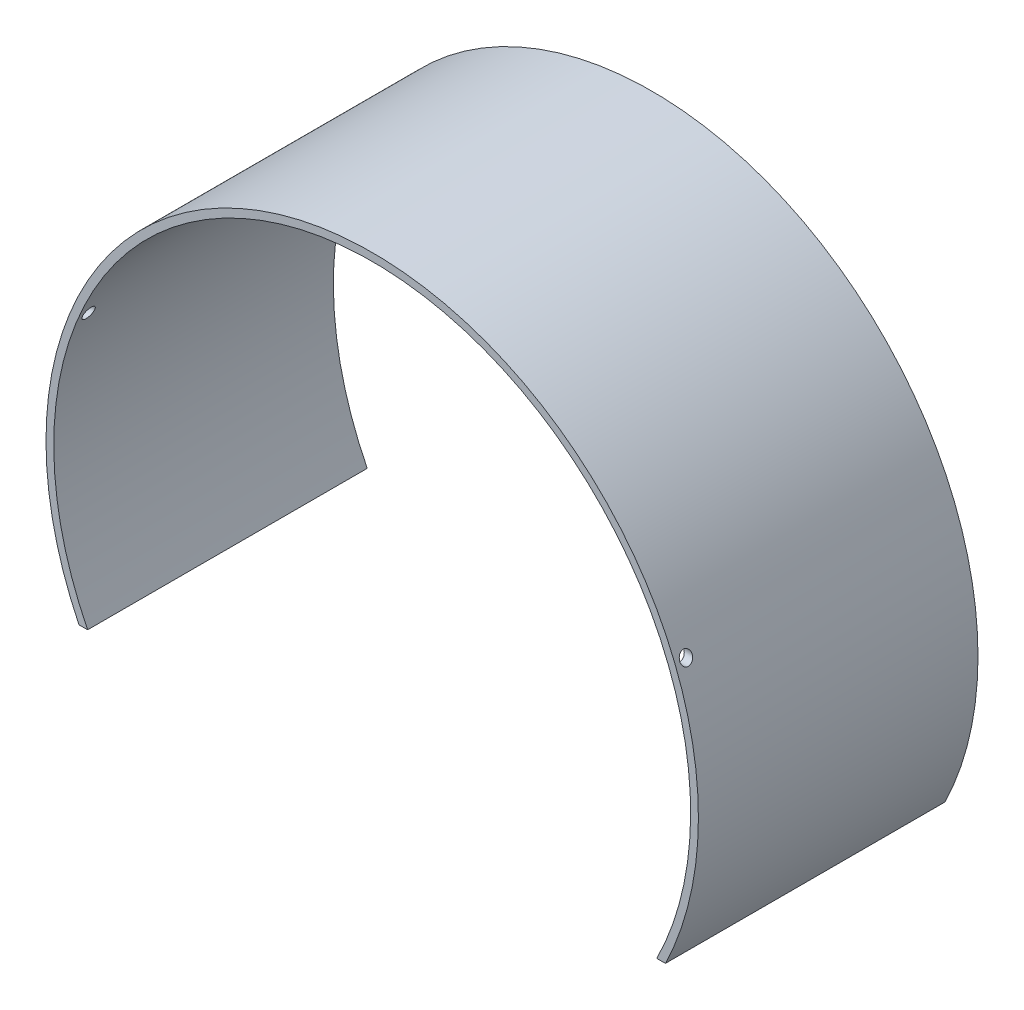
SolidWorks part; units mm, degrees
ref_plane "前视基准面" through (0, 0, 0) normal (0, 0, 1) x (1, 0, 0)
ref_plane "上视基准面" through (0, 0, 0) normal (0, 1, 0) x (1, 0, 0)
ref_plane "右视基准面" through (0, 0, 0) normal (1, 0, 0) x (0, 0, -1)
sketch "草图1" plane through (0, 0, 0) normal (0, 0, 1) x (1, 0, 0)
  arc A0 (-203, 0) -> (203, 0) centre (0, 0) ccw
  arc A1 (-210, 0) -> (210, 0) centre (0, 0) ccw
  arc A2 (-203, 0) -> (203, 0) centre (0, 0) ccw
  circle A3 centre (0, 0) radius 210
  circle A4 centre (0, 0) radius 203
  point P12 (0, 0)
extrude "凸台-拉伸2" add sketch "草图1" along normal blind 174
sketch "草图2" plane through (0, 0, 174) normal (0, 0, 1) x (1, 0, 0)
  line L0 (-173.7354, -102) -> (-170.7354, -102)
  line L1 (-170.7354, -102) -> (-170.7354, -105)
  line L2 (-170.7354, -105) -> (-173.7354, -105)
  line L3 (173.7354, -102) -> (170.7354, -102)
  line L4 (-173.7354, -102) -> (-175.5135, -102)
  line L6 (173.7354, -102) -> (175.5135, -102)
  line L7 (173.7354, -105) -> (170.7354, -105)
  line L8 (170.7354, -105) -> (170.7354, -102)
  circle A0 centre (0, 0) radius 203 construction
  arc A1 (0, -203) -> (-173.7354, -105) centre (0, 0) ccw
  circle M4 centre (0, 0) radius 203
extrude "凸台-拉伸4" add sketch "草图2" against normal up to surface (174 mm away) contours L0 L4 L2 L1 M4 | L8 L7 L6 L3 M4 up to face at (203, 0, 0)
sketch "草图3" plane through (0, 0, 174) normal (0, 0, 1) x (1, 0, 0)
  line L0 (-170.7354, -102) -> (238.3336, -102)
  line L1 (238.3336, -102) -> (254.3342, 272.2925)
  line L2 (254.3342, 272.2925) -> (-334.5694, 221.8511)
  line L3 (-170.7354, -102) -> (-306.8306, -102)
  line L4 (-306.8306, -102) -> (-334.5694, 221.8511)
extrude "切除-拉伸1" cut sketch "草图3" against normal blind 654
ref_plane "基准面1" through (0, -209.75, 0) normal (0, 1, 0) x (1, 0, 0)
sketch "草图5" plane through (0, 0, 174) normal (0, 0, 1) x (1, 0, 0)
  line L0 (0, -209.75) -> (120, -209.75)
  line L1 (95.7, -209.75) -> (-95.7, -209.75) construction
  line L2 (120, -209.75) -> (120, -172.0322)
  line L3 (0, -209.75) -> (-120, -209.75)
  line L4 (-120, -209.75) -> (-120, -172.0322)
  arc A0 (-120, -172.0322) -> (120, -172.0322) centre (0, 0) ccw
  arc M3 (-183.5647, -102) -> (183.5647, -102) centre (0, 0) ccw
extrude "凸台-拉伸5" add sketch "草图5" against normal up to surface (174 mm away) contours L4 L3 M3 | L0 L2 M3 up to face at (0, -129.25, 0)
sketch "草图6" plane through (0, 0, 174) normal (0, 0, 1) x (1, 0, 0)
  line L0 (-175.5135, -102) -> (-166.1957, -102)
  line L1 (175.5135, -102) -> (166.1957, -102)
  arc A0 (-166.1957, -102) -> (166.1957, -102) centre (0, 0) ccw
  arc A1 (-175.5135, -102) -> (175.5135, -102) centre (0, 0) ccw
extrude "凸台-拉伸6" add sketch "草图6" against normal up to surface (174 mm away) up to face at (0, -151.228, 0)
sketch "草图7" plane through (0, 0, 174) normal (0, 0, 1) x (1, 0, 0)
  line L0 (-166.9331, -92) -> (-166.9331, -95)
  line L1 (171.9331, -92) -> (166.9331, -92)
  line L2 (-171.9331, -92) -> (-166.9331, -92)
  line L3 (-188.4969, -92) -> (-171.9331, -92)
  line L4 (171.9331, -92) -> (188.4969, -92)
  line L5 (-166.9331, -95) -> (-170.2939, -95)
  line L6 (166.9331, -92) -> (166.9331, -95)
  line L7 (166.9331, -95) -> (170.2939, -95)
  arc A1 (-188.4969, -92) -> (188.4969, -92) centre (0, 0) ccw
  arc A2 (-170.2939, -95) -> (170.2939, -95) centre (0, 0) ccw
extrude "凸台-拉伸7" add sketch "草图7" against normal up to surface (174 mm away) up to face at (0, -169.2192, 0)
sketch "草图8" plane through (0, 0, 0) normal (0, 0, -1) x (-1, 0, 0)
  line L0 (166.9331, -92) -> (163.9331, -92)
  line L1 (163.9331, -92) -> (163.9331, -99)
  line L2 (163.9331, -99) -> (168, -99)
  line L3 (166.9331, -92) -> (166.9331, -95)
  line L4 (166.9331, -95) -> (170.2939, -95)
  line L6 (-166.9331, -95) -> (-170.2939, -95)
  line L7 (-166.9331, -92) -> (-166.9331, -95)
  line L8 (-163.9331, -99) -> (-168, -99)
  line L9 (-163.9331, -92) -> (-163.9331, -99)
  line L10 (-166.9331, -92) -> (-163.9331, -92)
  arc A0 (-170.2939, -95) -> (170.2939, -95) centre (0, 0) ccw construction
  arc A1 (168, -99) -> (170.2939, -95) centre (0, 0) ccw
  arc A2 (-168, -99) -> (-170.2939, -95) centre (0, 0) cw
extrude "凸台-拉伸8" add sketch "草图8" against normal up to surface (174 mm away) up to face at (0, -135.959, 174)
sketch "草图9" plane through (0, 0, 174) normal (0, 0, 1) x (1, 0, 0)
  line L0 (0, 0) -> (0, -337.2155)
  line L3 (-50, -195) -> (-50, -209.75)
  line L4 (-10.2439, -209.75) -> (-120, -209.75) construction
  line L5 (-50, -209.75) -> (50, -209.75)
  line L6 (10.2439, -209.75) -> (120, -209.75) construction
  line L7 (50, -209.75) -> (50, -195)
  line L8 (-50, -195) -> (-50, -182.2253)
  line L9 (-50, -182.2253) -> (50, -182.2253)
  line L10 (50, -182.2253) -> (50, -195)
  arc M4 (168, -99) -> (-168, -99) centre (0, 0) cw
  line M12 (-120, -209.75) -> (-10.2439, -209.75)
  line M14 (10.2439, -209.75) -> (120, -209.75)
extrude "切除-拉伸2" cut sketch "草图9" against normal blind 654 contours L9 L8 L0 M4 | L8 L3 L5 L0 M12 M4 | L10 L0 L5 L7 M4 M14 | L10 L9 L0 M4
sketch "草图10" plane through (0, -209.75, 0) normal (0, 1, 0) x (1, 0, 0)
  line L1 (-10.2439, 0) -> (10.2439, 0)
  line L2 (-10.2439, 0) -> (-10.2439, -174)
  line L3 (-10.2439, -174) -> (10.2439, -174)
  line L4 (10.2439, 0) -> (10.2439, -174)
extrude "切除-拉伸3" cut sketch "草图10" against normal mid plane 654
sketch "草图11" plane through (0, 0, 0) normal (0, 0, -1) x (-1, 0, 0)
  line L1 (18.7676, -16.6345) -> (254.4053, -16.6345)
  line L2 (18.7676, -16.6345) -> (18.7676, -265.8266)
  line L3 (18.7676, -265.8266) -> (254.4053, -265.8266)
  line L4 (254.4053, -16.6345) -> (254.4053, -265.8266)
extrude "切除-拉伸4" cut sketch "草图11" against normal blind 238
ref_plane "基准面2" through (0, 0, 209.75) normal (0, 0, 1) x (1, 0, 0)
sketch "草图14" plane through (0, 0, 209.75) normal (0, 0, 1) x (1, 0, 0)
  line L0 (188.4969, -92) -> (183.1966, -92)
  line L1 (0, 210) -> (0, 205)
  line L2 (183.1966, -92) -> (188.775, -92)
  arc A0 (183.1966, -92) -> (0, 205) centre (0, 0) ccw
  arc A1 (188.775, -92) -> (0, 210) centre (0, 0) ccw
extrude "凸台-拉伸10" add sketch "草图14" along normal blind 180 separate body contours A0 L1 A1 L2
sketch "草图17" plane through (0, -92, 0) normal (0, 1, 0) x (1, 0, 0)
  line L1 (-19.1853, 5.1617) -> (266.9134, 5.1617)
  line L2 (-19.1853, 5.1617) -> (-19.1853, -186.717)
  line L3 (-19.1853, -186.717) -> (266.9134, -186.717)
  line L4 (266.9134, 5.1617) -> (266.9134, -186.717)
extrude "切除-拉伸5" cut sketch "草图17" against normal blind 322
sketch "草图18" plane through (0, 0, 389.75) normal (0, 0, 1) x (1, 0, 0)
  line L0 (0, 210) -> (0, 205)
  line L1 (188.775, -92) -> (183.1966, -92)
  line L2 (-183.1966, -92) -> (-188.775, -92)
  arc A0 (0, 205) -> (-183.1966, -92) centre (0, 0) ccw
  arc A1 (0, 210) -> (-188.775, -92) centre (0, 0) ccw
  line M3 (0, 210) -> (0, 205)
extrude "凸台-拉伸11" add sketch "草图18" against normal up to surface (180 mm away) contours A1 L2 A0 M3 up to face at (134.6342, 83.6081, 209.75)
sketch "草图19" plane through (0, 0, 389.75) normal (0, 0, 1) x (1, 0, 0)
  line L0 (-188.775, -92) -> (188.775, -92)
  line L1 (0, -92) -> (0, 98)
  line L2 (0, 98) -> (195.9962, 98)
  line L3 (195.9962, 98) -> (-278.828, 98)
sketch "草图20" plane through (0, 0, 0) normal (1, 0, 0) x (0, 0, -1)
  circle A0 centre (-382.75, 78) radius 4
extrude "切除-拉伸7" cut sketch "草图20" against normal mid plane 1111
